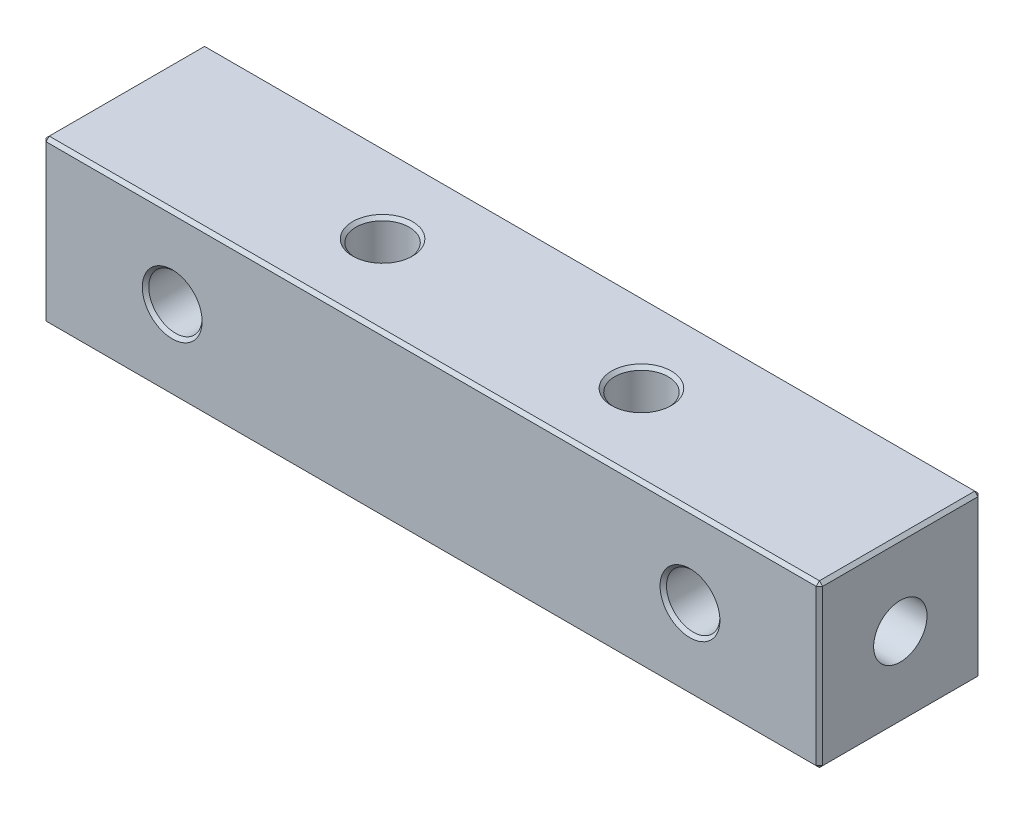
SolidWorks part; units mm, degrees
ref_plane "前视基准面" through (0, 0, 0) normal (0, 0, 1) x (1, 0, 0)
ref_plane "上视基准面" through (0, 0, 0) normal (0, 1, 0) x (1, 0, 0)
ref_plane "右视基准面" through (0, 0, 0) normal (1, 0, 0) x (0, 0, -1)
sketch "草图1" plane through (0, 0, 0) normal (0, 1, 0) x (1, 0, 0)
  line L1 (-24, 5) -> (24, 5)
  line L2 (-24, 5) -> (-24, -5)
  line L3 (-24, -5) -> (24, -5)
  line L4 (24, 5) -> (24, -5)
  line L5 (-24, 5) -> (24, -5) construction
  line L6 (-24, -5) -> (24, 5) construction
  point P0 (0, 0)
  dimension "D1" = 10
  dimension "D2" = 48
extrude "凸台-拉伸1" add sketch "草图1" along normal mid plane 10
hole_wizard "M4 螺纹孔1" positions "草图4" profile "草图6" tap size "M4" standard "GB" end condition through all
sketch "草图4" plane through (0, 5, 0) normal (0, 1, 0) x (1, 0, 0)
  line L1 (0, 0) -> (-50000, 0) construction
  line L2 (0, 0) -> (0, -50000) construction
  point P0 (-8, 0)
  point P2 (8, 0)
  point P15 (0, 0)
  dimension "D2" = 16
sketch "草图6" plane through (-8, 5, 0) normal (1, 0, 0) x (0, 0, 1)
  line L0 (0, 0) -> (0, 10)
  line L1 (0, 10) -> (1.65, 10)
  line L2 (1.65, 10) -> (1.65, 0)
  line L5 (1.65, 0) -> (0, 0)
  line L11 (0, -6.35) -> (0, 107.95) construction
  dimension "通孔螺纹孔钻头直径" = 3.3
  dimension "通孔螺纹孔钻头深度" = 10
cosmetic thread "孔螺蚊线1" parameters "D2"=4
cosmetic thread "孔螺蚊线7" parameters "D2"=4
hole_wizard "M4 螺纹孔2" positions "草图7" profile "草图8" tap size "M4" standard "GB" end condition through all
sketch "草图7" plane through (0, 0, -5) normal (0, 0, -1) x (-1, 0, 0)
  line L0 (0, 0) -> (-50000, 0) construction
  line L1 (-24, 5) -> (-24, -5) construction
  point P0 (-16, 0)
  point P2 (16, 0)
  dimension "D1" = 8
  dimension "D2" = 32
sketch "草图8" plane through (16, 0, -5) normal (1, 0, 0) x (0, 1, 0)
  line L0 (0, 0) -> (0, 10)
  line L1 (0, 10) -> (1.65, 10)
  line L2 (1.65, 10) -> (1.65, 0)
  line L5 (1.65, 0) -> (0, 0)
  line L11 (0, -6.35) -> (0, 107.95) construction
  dimension "通孔螺纹孔钻头直径" = 3.3
  dimension "通孔螺纹孔钻头深度" = 10
cosmetic thread "孔螺蚊线3" parameters "D2"=4
cosmetic thread "孔螺蚊线4" parameters "D2"=4
chamfer "倒角1" distance 0.2 angle 45 20 edges at (8, -5, 1.65) (-8, -5, 1.65) (-17.65, 0, 5) (14.35, 0, 5) (8, 5, 1.65) (-8, 5, 1.65) (-24, -5, 0) (24, -5, 0) (-24, 0, 5) (0, -5, 5) (24, 0, 5) (0, 5, 5) (-24, 5, 0) (24, 5, 0) (24, 0, -5) (0, 5, -5) (-24, 0, -5) (0, -5, -5) (-17.65, 0, -5) (14.35, 0, -5)
hole_wizard "M4 螺纹孔3" positions "草图9" profile "草图10" tap size "M4" standard "GB"
sketch "草图9" plane through (-24, 0, 0) normal (-1, 0, 0) x (0, 0, 1)
  point P0 (0, 0)
sketch "草图10" plane through (-24, 0, 0) normal (0, 1, 0) x (0, 0, 1)
  line L0 (0, 0) -> (0, 6.35)
  line L1 (0, 6.35) -> (1.65, 6.35)
  line L2 (1.65, 6.35) -> (1.65, 0)
  line L5 (1.65, 0) -> (0, 0)
  line L11 (0, -6.35) -> (0, 107.95) construction
  dimension "通孔螺纹孔钻头直径" = 3.3
  dimension "通孔螺纹孔钻头深度" = 6.35
cosmetic thread "孔螺蚊线5" parameters "D2"=4
hole_wizard "M4 螺纹孔4" positions "草图11" profile "草图12" tap size "M4" standard "GB"
sketch "草图11" plane through (24, 0, 0) normal (1, 0, 0) x (0, 0, -1)
  point P0 (0, 0)
sketch "草图12" plane through (24, 0, 0) normal (0, 1, 0) x (0, 0, -1)
  line L0 (0, 0) -> (0, 6.35)
  line L1 (0, 6.35) -> (1.65, 6.35)
  line L2 (1.65, 6.35) -> (1.65, 0)
  line L5 (1.65, 0) -> (0, 0)
  line L11 (0, -6.35) -> (0, 107.95) construction
  dimension "通孔螺纹孔钻头直径" = 3.3
  dimension "通孔螺纹孔钻头深度" = 6.35
cosmetic thread "孔螺蚊线6" parameters "D2"=4
